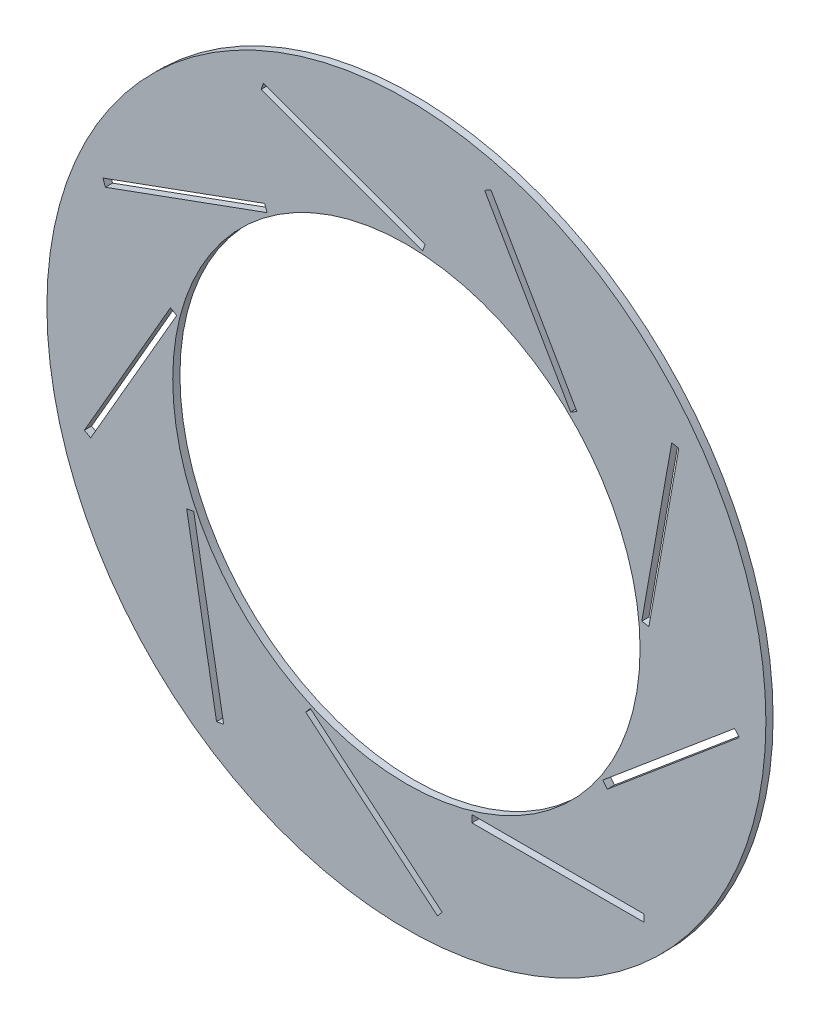
SolidWorks part; units mm, degrees
ref_plane "Front Plane" through (0, 0, 0) normal (0, 0, 1) x (1, 0, 0)
ref_plane "Top Plane" through (0, 0, 0) normal (0, 1, 0) x (1, 0, 0)
ref_plane "Right Plane" through (0, 0, 0) normal (1, 0, 0) x (0, 0, -1)
sketch "Sketch1" plane through (0, 0, 0) normal (0, 0, 1) x (1, 0, 0)
  circle A0 centre (0, 0) radius 150
  circle A1 centre (0, 0) radius 97.5
extrude "Shroud" add sketch "Sketch1" along normal blind 3
sketch "Sketch2" plane through (0, 0, 0) normal (0, 0, 1) x (1, 0, 0)
  line L0 (27.3244, -97.9181) -> (99.1067, -97.9181)
  line L1 (99.1067, -97.9181) -> (99.1067, -94.9181)
  line L2 (99.1067, -94.9181) -> (27.3244, -94.9181)
  line L3 (27.3244, -94.9181) -> (27.3244, -97.9181)
  line L4 (83.8722, -57.4459) -> (138.8607, -11.3051)
  line L5 (138.8607, -11.3051) -> (136.9323, -9.007)
  line L6 (136.9323, -9.007) -> (81.9439, -55.1478)
  line L7 (81.9439, -55.1478) -> (83.8722, -57.4459)
  line L8 (101.1754, 9.9059) -> (113.6402, 80.5977)
  line L9 (113.6402, 80.5977) -> (110.6858, 81.1187)
  line L10 (110.6858, 81.1187) -> (98.2209, 10.4269)
  line L11 (98.2209, 10.4269) -> (101.1754, 9.9059)
  line L12 (71.1374, 72.6227) -> (35.2463, 134.788)
  line L13 (35.2463, 134.788) -> (32.6482, 133.288)
  line L14 (32.6482, 133.288) -> (68.5393, 71.1227)
  line L15 (68.5393, 71.1227) -> (71.1374, 72.6227)
  line L16 (7.8135, 101.3584) -> (-59.6398, 125.9094)
  line L17 (-59.6398, 125.9094) -> (-60.6659, 123.0904)
  line L18 (-60.6659, 123.0904) -> (6.7874, 98.5394)
  line L19 (6.7874, 98.5394) -> (7.8135, 101.3584)
  line L20 (-59.1665, 82.6675) -> (-126.6198, 58.1165)
  line L21 (-126.6198, 58.1165) -> (-125.5937, 55.2974)
  line L22 (-125.5937, 55.2974) -> (-58.1404, 79.8484)
  line L23 (-58.1404, 79.8484) -> (-59.1665, 82.6675)
  line L24 (-98.4618, 25.2955) -> (-134.3529, -36.8698)
  line L25 (-134.3529, -36.8698) -> (-131.7549, -38.3698)
  line L26 (-131.7549, -38.3698) -> (-95.8637, 23.7955)
  line L27 (-95.8637, 23.7955) -> (-98.4618, 25.2955)
  line L28 (-91.6857, -43.9126) -> (-79.2209, -114.6043)
  line L29 (-79.2209, -114.6043) -> (-76.2664, -114.0834)
  line L30 (-76.2664, -114.0834) -> (-88.7313, -43.3916)
  line L31 (-88.7313, -43.3916) -> (-91.6857, -43.9126)
  line L32 (-42.0089, -92.5734) -> (12.9795, -138.7142)
  line L33 (12.9795, -138.7142) -> (14.9079, -136.4161)
  line L34 (14.9079, -136.4161) -> (-40.0805, -90.2753)
  line L35 (-40.0805, -90.2753) -> (-42.0089, -92.5734)
extrude "Blade_slots" cut sketch "Sketch2" along normal blind 3
